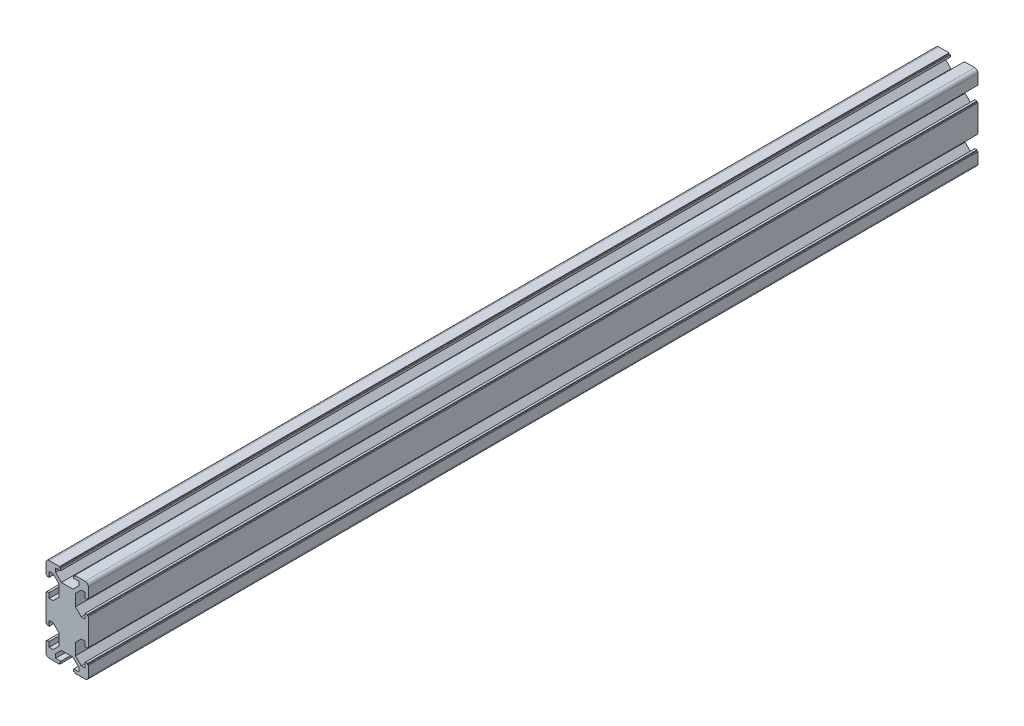
SolidWorks part; units mm, degrees
ref_plane "Plane1" through (0, 0, 0) normal (0, 0, 1) x (1, 0, 0)
ref_plane "Plane2" through (0, 0, 0) normal (0, 1, 0) x (1, 0, 0)
ref_plane "Plane3" through (0, 0, 0) normal (1, 0, 0) x (0, 0, -1)
sketch "Sketch1" plane through (0, 0, 0) normal (0, 0, 1) x (1, 0, 0)
  line L0 (-3.6, 10) -> (-3.6, 9.5)
  line L1 (-3.6, 9.5) -> (-3.1, 9.5)
  line L2 (-3.1, 9.5) -> (-3.1, 8.5)
  line L3 (-3.1, 8.5) -> (-5.5, 8.5)
  line L4 (8.85, -10) -> (2.75, -3.9)
  line L5 (-10, -16.4) -> (-10, -3.6)
  line L6 (8.5, 10) -> (3.6, 10)
  line L7 (10, 8.5) -> (10, 3.6)
  line L8 (0, 14.8756) -> (0, 0) construction
  line L9 (0, 0) -> (10, 0) construction
  line L10 (-5.5, 8.5) -> (-5.5, 6.65)
  line L11 (-5.5, 6.65) -> (-2.75, 3.9)
  line L12 (-2.75, 3.9) -> (2.75, 3.9)
  line L13 (5.5, 6.65) -> (2.75, 3.9)
  line L14 (5.5, 8.5) -> (5.5, 6.65)
  line L15 (3.1, 8.5) -> (5.5, 8.5)
  line L16 (3.1, 9.5) -> (3.1, 8.5)
  line L17 (3.6, 9.5) -> (3.1, 9.5)
  line L18 (3.6, 10) -> (3.6, 9.5)
  line L19 (-3.6, 10) -> (-8.5, 10)
  line L20 (10, 3.6) -> (9.5, 3.6)
  line L21 (9.5, 3.6) -> (9.5, 3.1)
  line L22 (9.5, 3.1) -> (8.5, 3.1)
  line L23 (8.5, 3.1) -> (8.5, 5.5)
  line L24 (8.5, 5.5) -> (6.65, 5.5)
  line L25 (6.65, 5.5) -> (3.9, 2.75)
  line L26 (3.9, 2.75) -> (3.9, -2.75)
  line L27 (6.65, -5.5) -> (3.9, -2.75)
  line L28 (8.5, -5.5) -> (6.65, -5.5)
  line L29 (8.5, -3.1) -> (8.5, -5.5)
  line L30 (9.5, -3.1) -> (8.5, -3.1)
  line L31 (9.5, -3.6) -> (9.5, -3.1)
  line L32 (10, -3.6) -> (9.5, -3.6)
  line L33 (8.85, -10) -> (2.75, -16.1)
  line L34 (-8.85, -10) -> (-2.75, -16.1)
  line L35 (-8.85, -10) -> (-2.75, -3.9)
  line L39 (2.75, -3.9) -> (-2.75, -3.9)
  line L46 (-10, -3.6) -> (-9.5, -3.6)
  line L47 (-9.5, -3.6) -> (-9.5, -3.1)
  line L48 (-9.5, -3.1) -> (-8.5, -3.1)
  line L49 (-8.5, -3.1) -> (-8.5, -5.5)
  line L50 (-8.5, -5.5) -> (-6.65, -5.5)
  line L51 (-6.65, -5.5) -> (-3.9, -2.75)
  line L52 (-3.9, -2.75) -> (-3.9, 2.75)
  line L53 (-6.65, 5.5) -> (-3.9, 2.75)
  line L54 (-8.5, 5.5) -> (-6.65, 5.5)
  line L55 (-8.5, 3.1) -> (-8.5, 5.5)
  line L56 (-9.5, 3.1) -> (-8.5, 3.1)
  line L57 (-9.5, 3.6) -> (-9.5, 3.1)
  line L58 (-10, 3.6) -> (-9.5, 3.6)
  line L60 (-10, 3.6) -> (-10, 8.5)
  line L61 (10, -3.6) -> (10, -16.4)
  line L66 (-8.5, -30) -> (-3.6, -30)
  line L67 (-10, -28.5) -> (-10, -23.6)
  line L72 (-2.75, -16.1) -> (2.75, -16.1)
  line L80 (10, -16.4) -> (9.5, -16.4)
  line L81 (9.5, -16.4) -> (9.5, -16.9)
  line L82 (9.5, -16.9) -> (8.5, -16.9)
  line L83 (8.5, -16.9) -> (8.5, -14.5)
  line L84 (8.5, -14.5) -> (6.65, -14.5)
  line L85 (6.65, -14.5) -> (3.9, -17.25)
  line L86 (3.9, -17.25) -> (3.9, -22.75)
  line L87 (6.65, -25.5) -> (3.9, -22.75)
  line L88 (8.5, -25.5) -> (6.65, -25.5)
  line L89 (8.5, -23.1) -> (8.5, -25.5)
  line L90 (9.5, -23.1) -> (8.5, -23.1)
  line L91 (9.5, -23.6) -> (9.5, -23.1)
  line L92 (10, -23.6) -> (9.5, -23.6)
  line L93 (3.6, -30) -> (3.6, -29.5)
  line L94 (3.6, -29.5) -> (3.1, -29.5)
  line L95 (3.1, -29.5) -> (3.1, -28.5)
  line L96 (3.1, -28.5) -> (5.5, -28.5)
  line L97 (5.5, -28.5) -> (5.5, -26.65)
  line L98 (5.5, -26.65) -> (2.75, -23.9)
  line L99 (2.75, -23.9) -> (-2.75, -23.9)
  line L100 (-5.5, -26.65) -> (-2.75, -23.9)
  line L101 (-5.5, -28.5) -> (-5.5, -26.65)
  line L102 (-3.1, -28.5) -> (-5.5, -28.5)
  line L103 (-3.1, -29.5) -> (-3.1, -28.5)
  line L104 (-3.6, -29.5) -> (-3.1, -29.5)
  line L105 (-3.6, -30) -> (-3.6, -29.5)
  line L106 (-10, -23.6) -> (-9.5, -23.6)
  line L107 (-9.5, -23.6) -> (-9.5, -23.1)
  line L108 (-9.5, -23.1) -> (-8.5, -23.1)
  line L109 (-8.5, -23.1) -> (-8.5, -25.5)
  line L110 (-8.5, -25.5) -> (-6.65, -25.5)
  line L111 (-6.65, -25.5) -> (-3.9, -22.75)
  line L112 (-3.9, -22.75) -> (-3.9, -17.25)
  line L113 (-6.65, -14.5) -> (-3.9, -17.25)
  line L114 (-8.5, -14.5) -> (-6.65, -14.5)
  line L115 (-8.5, -16.9) -> (-8.5, -14.5)
  line L116 (-9.5, -16.9) -> (-8.5, -16.9)
  line L117 (-9.5, -16.4) -> (-9.5, -16.9)
  line L118 (-10, -16.4) -> (-9.5, -16.4)
  line L119 (3.6, -30) -> (8.5, -30)
  line L121 (10, -23.6) -> (10, -28.5)
  line L122 (0, -20) -> (10, -20) construction
  line L123 (-20.8285, -10) -> (-3.6, -10) [skipped]
  line L124 (3.6, -10) -> (3.6, -9.5) [skipped]
  line L125 (3.6, -10) -> (3.6, -9.5) [skipped]
  line L126 (3.6, -9.5) -> (3.1, -9.5) [skipped]
  line L127 (3.6, -9.5) -> (3.1, -9.5) [skipped]
  line L128 (3.1, -9.5) -> (3.1, -8.5) [skipped]
  line L129 (3.1, -9.5) -> (3.1, -8.5) [skipped]
  line L130 (3.1, -8.5) -> (5.5, -8.5) [skipped]
  line L131 (3.1, -8.5) -> (5.5, -8.5) [skipped]
  line L132 (-3.1, -8.5) -> (-5.5, -8.5) [skipped]
  line L133 (-3.1, -8.5) -> (-5.5, -8.5) [skipped]
  line L134 (-3.1, -9.5) -> (-3.1, -8.5) [skipped]
  line L135 (-3.1, -9.5) -> (-3.1, -8.5) [skipped]
  line L136 (-3.6, -9.5) -> (-3.1, -9.5) [skipped]
  line L137 (-3.6, -9.5) -> (-3.1, -9.5) [skipped]
  line L138 (-3.6, -10) -> (-3.6, -9.5) [skipped]
  line L139 (-3.6, -10) -> (-3.6, -9.5) [skipped]
  line L140 (3.6, -10) -> (14.9874, -10) [skipped]
  line L141 (-3.6, -10) -> (-3.6, -10.5) [skipped]
  line L142 (-3.6, -10.5) -> (-3.1, -10.5) [skipped]
  line L143 (-3.1, -10.5) -> (-3.1, -11.5) [skipped]
  line L144 (-3.1, -11.5) -> (-5.5, -11.5) [skipped]
  line L145 (8.5, -10) -> (3.6, -10) [skipped]
  line L146 (3.1, -11.5) -> (5.5, -11.5) [skipped]
  line L147 (3.1, -10.5) -> (3.1, -11.5) [skipped]
  line L148 (3.6, -10.5) -> (3.1, -10.5) [skipped]
  line L149 (3.6, -10) -> (3.6, -10.5) [skipped]
  line L150 (-3.6, -10) -> (-8.5, -10) [skipped]
  line L151 (-10, -16.4) -> (-10, -11.5) [skipped]
  line L152 (10, -11.5) -> (10, -16.4) [skipped]
  line L153 (-5.5, -8.5) -> (-5.5, -6.65) [skipped]
  line L154 (-5.5, -8.5) -> (-5.5, -6.65) [skipped]
  line L155 (5.5, -8.5) -> (5.5, -6.65) [skipped]
  line L156 (5.5, -8.5) -> (5.5, -6.65) [skipped]
  line L157 (5.5, -11.5) -> (5.5, -13.35) [skipped]
  line L158 (-5.5, -11.5) -> (-5.5, -13.35) [skipped]
  line L159 (-12.2446, -13.3946) -> (-10, -11.15) [skipped]
  line L160 (-12.2446, -13.3946) -> (-10, -11.15) [skipped]
  line L161 (13.644, -5.206) -> (10, -8.85) [skipped]
  line L162 (12.1963, -13.3463) -> (10, -11.15) [skipped]
  line L163 (12.1963, -13.3463) -> (10, -11.15) [skipped]
  line L164 (-11.1344, -7.7156) -> (-10, -8.85) [skipped]
  circle A0 centre (0, 0) radius 2.5
  arc A1 (-10, 8.5) -> (-8.5, 10) centre (-8.5, 8.5) cw
  arc A2 (10, 8.5) -> (8.5, 10) centre (8.5, 8.5) ccw
  arc A3 (10, -28.5) -> (8.5, -30) centre (8.5, -28.5) cw
  arc A4 (-10, -28.5) -> (-8.5, -30) centre (-8.5, -28.5) ccw
  circle A5 centre (0, -20) radius 2.5
  arc A10 (-8.5, -10) -> (-10, -16.2676) centre (-13.642, -12.0827) cw [skipped]
  arc A11 (8.5, -10) -> (10, -11.9856) centre (9.9185, -10.4878) ccw [skipped]
  arc A12 (-10, -11.5) -> (-8.5, -10) centre (-8.5, -11.5) cw [skipped]
  arc A13 (10, -11.5) -> (8.5, -10) centre (8.5, -11.5) ccw [skipped]
  arc A14 (8.5, -30) -> (10, -31.9856) centre (9.9185, -30.4878) ccw [skipped]
  arc A15 (-8.5, -30) -> (-10, -36.2676) centre (-13.642, -32.0827) cw [skipped]
  point P0 (-10, 0)
  point P1 (10, 0)
  point P2 (0, 10)
  point P4 (0, 0)
  point P5 (0, -10)
  point P6 (-10, -10)
  point P7 (10, 10)
  point P8 (-10, 10)
  point P12 (-10, -10)
  point P13 (10, -10)
  point P15 (0, -10)
  point P16 (10, -10)
  point P36 (-10, 10)
  point P39 (10, 10)
  point P43 (-10, -20)
  point P44 (10, -20)
  point P88 (0, -30)
  point P89 (0, -20)
  point P90 (-10, -30)
  point P91 (10, -30)
extrude "凸台-拉伸1" add sketch "Sketch1" along normal blind 420 contours L19 A1 L60 L58 L57 L56 L55 L54 L53 L52 L51 L50 L49 L48 L47 L46 L5 L118 L117 L116 L115 L114 L113 L112 L111 L110 L109 L108 L107 L106 L67 A4 L66 L105 L104 L103 L102 L101 L100 L99 L98 L97 L96 L95 L94 L93 L119 A3 L121 L92 L91 L90 L89 L88 L87 L86 L85 L84 L83 L82 L81 L80 L61 L32 L31 L30 L29 L28 L27 L26 L25 L24 L23 L22 L21 L20 L7 A2 L6 L18 L17 L16 L15 L14 L13 L12 L11 L10 L3 L2 L1 L0
